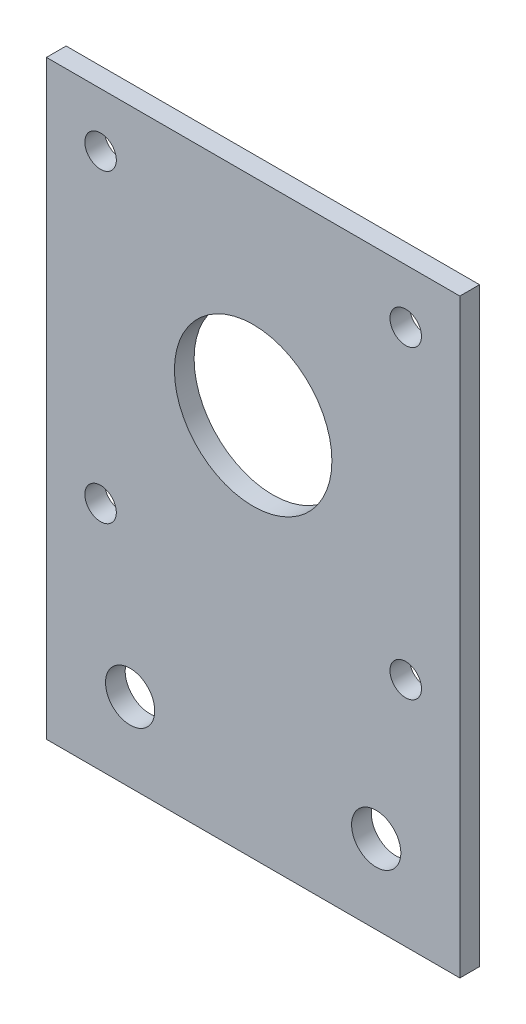
SolidWorks part; units mm, degrees
ref_plane "前视基准面" through (0, 0, 0) normal (0, 0, 1) x (1, 0, 0)
ref_plane "上视基准面" through (0, 0, 0) normal (0, 1, 0) x (1, 0, 0)
ref_plane "右视基准面" through (0, 0, 0) normal (1, 0, 0) x (0, 0, -1)
sketch "草图1" plane through (0, 0, 0) normal (0, 0, 1) x (1, 0, 0)
  line L0 (21, 21) -> (-21, 21)
  line L1 (-21, 21) -> (-21, -39)
  line L2 (-21, -39) -> (21, -39)
  line L3 (0, 18.109) -> (0, 11.3238) construction
  line L4 (21, 21) -> (21, -39)
  circle A0 centre (0, 0) radius 8
  circle A1 centre (-15.5, 15.5) radius 1.6
  circle A2 centre (-15.5, -15.5) radius 1.6
  circle A3 centre (-12.5, -31) radius 2.5
  circle A4 centre (15.5, 15.5) radius 1.6
  circle A5 centre (15.5, -15.5) radius 1.6
  circle A6 centre (12.5, -31) radius 2.5
  point P11 (-15.5, 15.5)
  point P12 (-15.5, -15.5)
  point P15 (-12.5, -31)
  point P25 (0, -39)
  point P26 (0, 21)
  dimension "D1" = 21
  dimension "D6" = 8
  dimension "D2" = 60
  dimension "D3" = 21
  dimension "D4" = 15.5
  dimension "D5" = 31
  dimension "D7" = 12.5
extrude "凸台-拉伸1" add sketch "草图1" along normal blind 2
